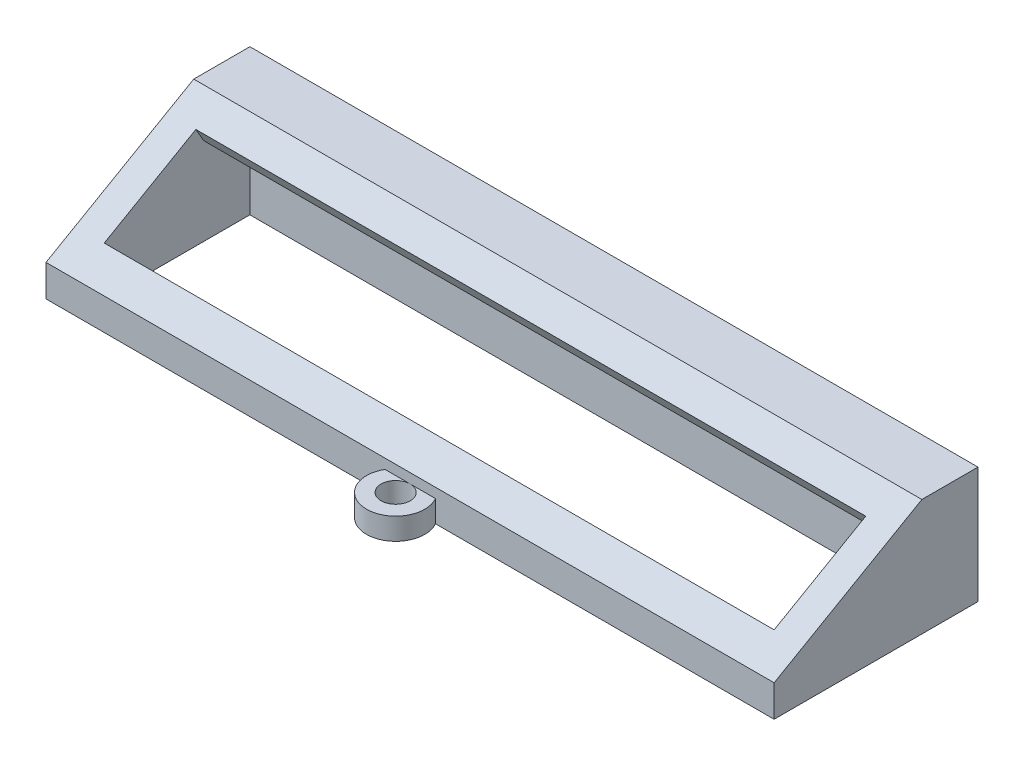
SolidWorks part; units mm, degrees
ref_plane "前基準面" through (0, 0, 0) normal (0, 0, 1) x (1, 0, 0)
ref_plane "上基準面" through (0, 0, 0) normal (0, 1, 0) x (1, 0, 0)
ref_plane "右基準面" through (0, 0, 0) normal (1, 0, 0) x (0, 0, -1)
sketch "草圖1" plane through (0, 0, 0) normal (0, 1, 0) x (1, 0, 0)
  line L1 (-250, 70) -> (250, 70)
  line L2 (-250, 70) -> (-250, -70)
  line L3 (-250, -70) -> (250, -70)
  line L4 (250, 70) -> (250, -70)
  line L5 (-250, 70) -> (250, -70) construction
  line L6 (-250, -70) -> (250, 70) construction
  point P0 (0, 0)
  dimension "D1" = 500
  dimension "D2" = 140
extrude "填料-伸長1" add sketch "草圖1" along normal blind 80
sketch "草圖2" plane through (0, 0, 0) normal (0, -1, 0) x (1, 0, 0)
  line L0 (-250, 70) -> (250, 70) construction
  line L1 (230, 50) -> (-230, 50)
  line L2 (230, 50) -> (230, -50)
  line L3 (230, -50) -> (-230, -50)
  line L4 (-230, 50) -> (-230, -50)
  line L5 (230, 50) -> (-230, -50) construction
  line L6 (230, -50) -> (-230, 50) construction
  line L7 (250, 70) -> (250, -70) construction
  point P0 (0, 0)
  dimension "D1" = 20
  dimension "D2" = 20
extrude "除料-伸長1" cut sketch "草圖2" against normal blind 60
sketch "草圖6" plane through (0, 0, 0) normal (0, -1, 0) x (1, 0, 0)
  line L0 (0, -950) -> (0, 49050) construction
  line L1 (230, 50) -> (-230, 50) construction
  line L2 (-250, 70) -> (250, 70) construction
  line L3 (-1.1955, 70) -> (1.4235, 70) construction
  line L4 (-1.1955, 70) -> (-1.1955, 80) construction
  line L5 (-1.1955, 80) -> (1.4235, 80) construction
  line L6 (1.4235, 70) -> (1.4235, 80) construction
  circle A0 centre (0.114, 80) radius 10
  point P5 (0, 50)
  dimension "D2" = 20
  dimension "D1" = 10
extrude "伸長-薄件4" add sketch "草圖6" against normal blind 15 thin
sketch "草圖7" plane through (250, 0, 0) normal (1, 0, 0) x (0, 0, -1)
  line L0 (-70, 21.7294) -> (31.4571, 80)
  line L1 (-70, 80) -> (-70, 0) construction
  line L2 (-70, 80) -> (70, 80) construction
  line L3 (31.4571, 80) -> (-70, 80)
  line L4 (-70, 80) -> (-70, 21.7294)
extrude "除料-伸長2" cut sketch "草圖7" against normal through all
sketch "草圖8" plane through (0, 46.571, 26.7474) normal (0, 0.8672, 0.498) x (1, 0, 0)
  line L1 (-230, 26.9638) -> (230, 26.9638)
  line L2 (-230, 26.9638) -> (-230, 45.7291)
  line L3 (-230, 45.7291) -> (230, 45.7291)
  line L4 (230, 26.9638) -> (230, 45.7291)
extrude "除料-伸長3" cut sketch "草圖8" against normal blind 15
